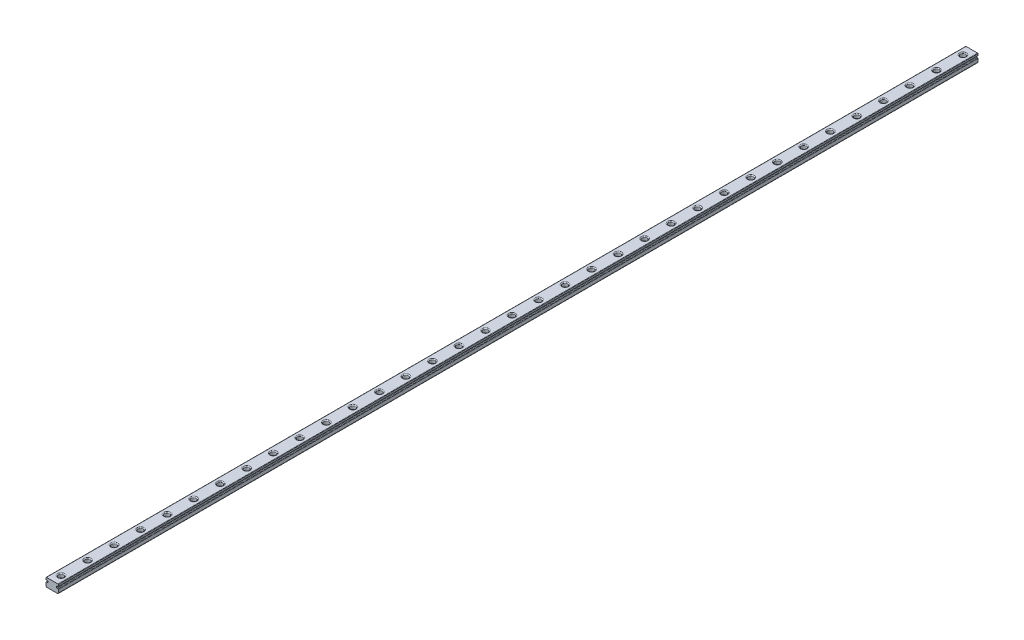
SolidWorks part; units mm, degrees
material "201 退火不锈钢 (SS)"
ref_plane "前视基准面" through (0, 0, 0) normal (0, 0, 1) x (1, 0, 0)
ref_plane "上视基准面" through (0, 0, 0) normal (0, 1, 0) x (1, 0, 0)
ref_plane "右视基准面" through (0, 0, 0) normal (1, 0, 0) x (0, 0, -1)
sketch "草图1" plane through (0, 0, 0) normal (0, 0, 1) x (1, 0, 0)
  line L0 (0, 0) -> (7, 0)
  line L1 (0, 3.5) -> (0, 4.8)
  line L2 (0, 4.8) -> (7, 4.8)
  line L3 (7, 4.8) -> (7, 3.5)
  line L4 (0, 4.8) -> (0, 3.5)
  line L5 (0, 2.5) -> (1, 2.5)
  line L6 (1, 2.5) -> (1, 3.5)
  line L7 (1, 3.5) -> (0, 3.5)
  line L8 (7, 3.5) -> (6, 3.5)
  line L9 (6, 3.5) -> (6, 2.5)
  line L10 (6, 2.5) -> (7, 2.5)
  line L11 (0, 2.5) -> (0, 0)
  line L12 (7, 2.5) -> (7, 0)
extrude "凸台-拉伸1" add sketch "草图1" along normal blind 550 contours L12 L10 L9 L8 L3 L2 L1 L7 L6 L5 L11 L0
fillet "圆角1" radius 0.25 10 edges at (7, 2.5, 275) (0, 2.5, 275) (1, 3.5, 275) (1, 2.5, 275) (6, 2.5, 275) (6, 3.5, 275) (7, 4.8, 275) (0, 4.8, 275) (0, 3.5, 275) (7, 3.5, 275)
fillet "圆角2" radius 0.5 2 edges at (0, 0, 275) (7, 0, 275)
sketch "草图2" plane through (0, 4.8, 0) normal (0, 1, 0) x (1, 0, 0)
  line L0 (0.25, 0) -> (6.75, 0) construction
  line L1 (3.5, 0) -> (3.5, -6.7471) construction
  circle A0 centre (3.5, -5) radius 1.5
  dimension "D1" = 3
  dimension "D2" = 5
extrude "切除-拉伸1" cut sketch "草图2" against normal blind 2.3
sketch "草图3" plane through (0, 2.5, 0) normal (0, 1, 0) x (1, 0, 0)
  line L0 (0.5, 0) -> (6.5, 0) construction
  line L1 (3.5, 0) -> (3.5, -4.4975) construction
  circle A1 centre (3.5, -5) radius 1.2
  dimension "D1" = 2.4
extrude "切除-拉伸2" cut sketch "草图3" against normal through all
fillet "圆角3" radius 0.5 1 edges at (3.5, 4.8, 6.5)
pattern_linear "阵列(线性)2" count 37 spacing 15 along (0, 0, 1) of "切除-拉伸1", "切除-拉伸2", "圆角3"
sketch "草图4" plane through (0, 0, 550) normal (0, 0, 1) x (1, 0, 0)
  line L1 (-0.1519, 5.0948) -> (7.4555, 5.0948)
  line L2 (-0.1519, 5.0948) -> (-0.1519, -0.4394)
  line L3 (-0.1519, -0.4394) -> (7.4555, -0.4394)
  line L4 (7.4555, 5.0948) -> (7.4555, -0.4394)
extrude "切除-拉伸3" cut sketch "草图4" against normal blind 30
